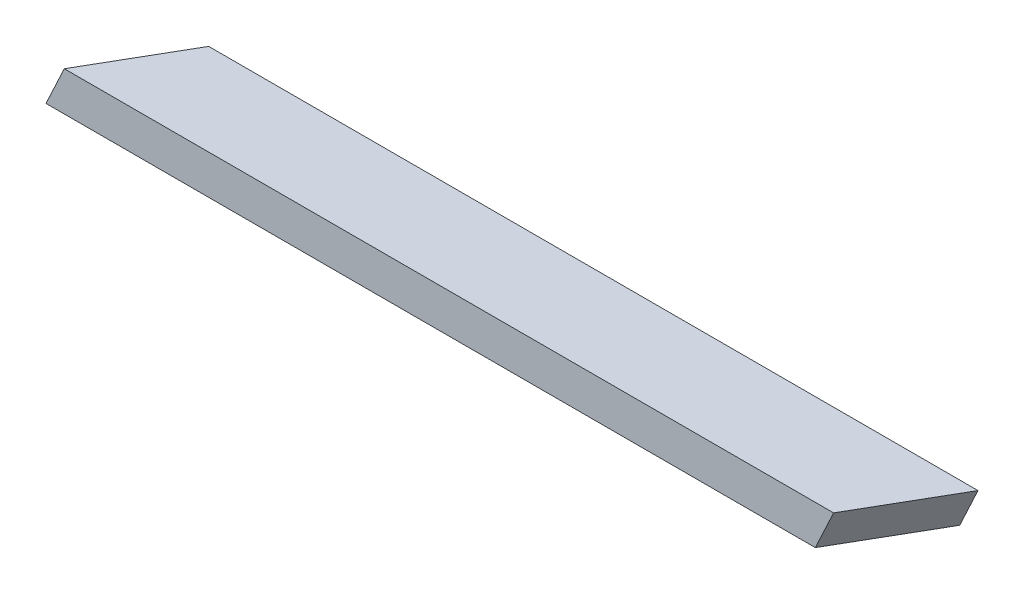
SolidWorks part; units mm, degrees
material "Pine"
ref_plane "Front Plane" through (0, 0, 0) normal (0, 0, 1) x (1, 0, 0)
ref_plane "Top Plane" through (0, 0, 0) normal (0, 1, 0) x (1, 0, 0)
ref_plane "Right Plane" through (0, 0, 0) normal (1, 0, 0) x (0, 0, -1)
ref_plane "Plane7" through (0, 0, 44.45) normal (0, 0, 1) x (1, 0, 0)
sketch "Sketch10" plane through (0, 0, 0) normal (0, 1, 0) x (1, 0, 0)
  line L0 (-373.59, 44.45) -> (-424.9164, -44.45)
  line L1 (373.59, -44.45) -> (-373.59, -44.45)
  line L2 (373.59, -44.45) -> (373.59, 44.45)
  line L3 (373.59, 44.45) -> (-373.59, 44.45)
  line L4 (-373.59, -44.45) -> (-373.59, 44.45)
  line L5 (373.59, -44.45) -> (-373.59, 44.45) construction
  line L6 (373.59, 44.45) -> (-373.59, -44.45) construction
  line L7 (-424.9164, -44.45) -> (-373.59, -44.45)
  line L8 (-373.59, -44.45) -> (-373.59, 44.45)
  line L9 (373.59, 44.45) -> (322.2636, -44.45)
  line L10 (322.2636, -44.45) -> (373.59, -44.45)
  point P0 (0, 0)
  dimension "D1" = 747.18
  dimension "D2" = 88.9
  dimension "D3" = 120
sketch "Sketch11" plane through (0, 0, 44.45) normal (0, 0, 1) x (1, 0, 0)
  line L0 (373.59, 0) -> (-373.59, 0) construction
  line L1 (322.2636, 0) -> (-424.9164, 0)
  line L2 (322.2636, 0) -> (322.2636, 38.1)
  line L3 (322.2636, 38.1) -> (-424.9164, 38.1)
  line L4 (-424.9164, 0) -> (-424.9164, 38.1)
  line L5 (373.59, 0) -> (-373.59, 0) construction
  line L6 (-424.9164, 0) -> (-373.59, 0) construction
  line L7 (-424.9164, 0) -> (-407.1501, 38.1)
  line L8 (-407.1501, 38.1) -> (-424.9164, 38.1)
  line L9 (-424.9164, 0) -> (-424.9164, 38.1)
  line L10 (322.2636, 0) -> (340.0299, 38.1)
  line L11 (340.0299, 38.1) -> (322.2636, 38.1)
  line L12 (322.2636, 38.1) -> (322.2636, 0)
  dimension "D1" = 38.1
  dimension "D2" = 115
extrude "Boss-Extrude1" add sketch "Sketch11" along direction (-0.5, 0, 0.866) on the side against the normal up to vertex (88.9 mm away) contours L7 L1 L2 L3 | L10 L11 L2
